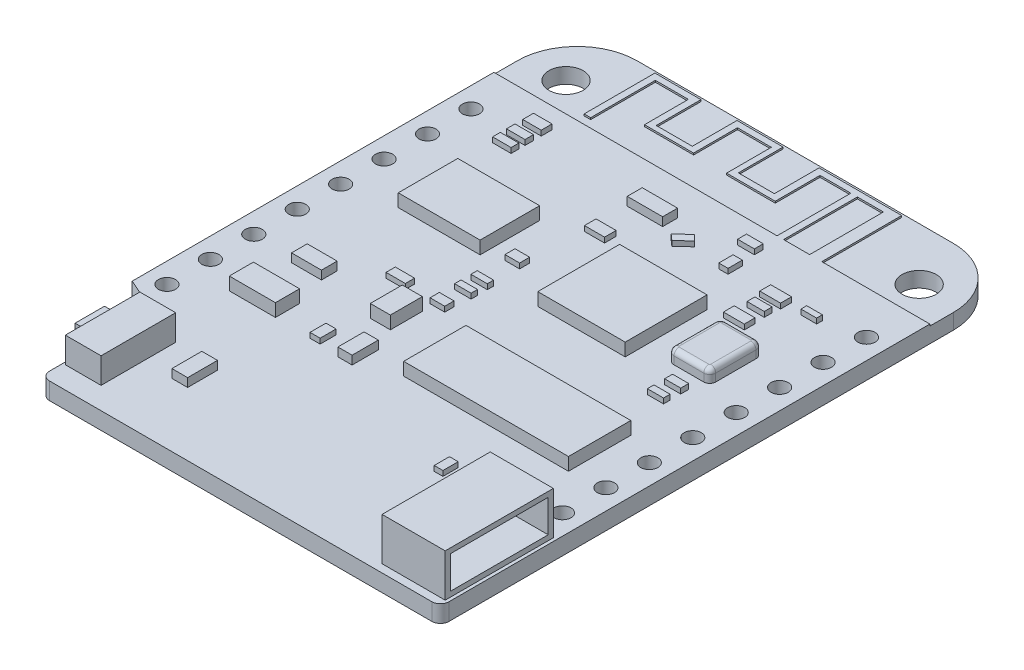
SolidWorks part; units mm, degrees
ref_plane "Front Plane" through (0, 0, 0) normal (0, 0, 1) x (1, 0, 0)
ref_plane "Top Plane" through (0, 0, 0) normal (0, 1, 0) x (1, 0, 0)
ref_plane "Right Plane" through (0, 0, 0) normal (1, 0, 0) x (0, 0, -1)
sketch "Sketch2"
sketch "Sketch4" plane through (0, 0, 0) normal (0, 1, 0) x (1, 0, 0)
  line L4 (0, 25.3183) -> (0, -8.1817) construction
  line L5 (-9.25, 25.3183) -> (9.25, 25.3183)
  line L6 (-12.75, 21.8183) -> (-12.75, -0.7087)
  line L7 (-10.1117, -8.1817) -> (12.25, -8.1817)
  line L27 (12.75, 21.8183) -> (12.75, -7.6817)
  line L28 (-12.75, -0.7087) -> (-10.9103, -1.5185)
  line L29 (-10.6117, -1.9761) -> (-10.6117, -7.6817)
  arc A2 (-9.25, 25.3183) -> (-12.75, 21.8183) centre (-9.25, 21.8183) ccw
  arc A3 (9.25, 25.3183) -> (12.75, 21.8183) centre (9.25, 21.8183) cw
  arc A31 (12.25, -8.1817) -> (12.75, -7.6817) centre (12.25, -7.6817) ccw
  arc A32 (-10.9103, -1.5185) -> (-10.6117, -1.9761) centre (-11.1117, -1.9761) cw
  arc A33 (-10.6117, -7.6817) -> (-10.1117, -8.1817) centre (-10.1117, -7.6817) ccw
  circle A35 centre (-11.5663, 17.9202) radius 0.5
  circle A36 centre (-11.5663, 15.3802) radius 0.5
  circle A37 centre (-11.5663, 12.8402) radius 0.5
  circle A38 centre (-11.5663, 10.3002) radius 0.5
  circle A39 centre (-11.5663, 7.7602) radius 0.5
  circle A40 centre (-11.5663, 5.2202) radius 0.5
  circle A41 centre (-11.5663, 2.6802) radius 0.5
  circle A42 centre (-11.5663, 0.1402) radius 0.5
  circle A43 centre (11.5663, 0.1402) radius 0.5
  circle A44 centre (11.5663, 2.6802) radius 0.5
  circle A45 centre (11.5663, 5.2202) radius 0.5
  circle A46 centre (11.5663, 7.7602) radius 0.5
  circle A47 centre (11.5663, 10.3002) radius 0.5
  circle A48 centre (11.5663, 12.8402) radius 0.5
  circle A49 centre (11.5663, 15.3802) radius 0.5
  circle A50 centre (11.5663, 17.9202) radius 0.5
  circle A51 centre (10.3263, 22.2414) radius 1
  circle A52 centre (-10.3263, 22.2414) radius 1
  point P8 (12.75, -8.1817)
  point P13 (-12.75, 25.3183)
  point P16 (12.75, 25.3183)
  dimension "D2" = 25.5
  dimension "D3" = 3.5
  dimension "D5" = 1
  dimension "D4" = 0.5
  dimension "D7" = 2
  dimension "D6" = 8
  dimension "D1" = 33.5
extrude "Boss-Extrude1" add sketch "Sketch4" against normal blind 1
sketch "Sketch5" plane through (0, 0, 0) normal (0, 1, 0) x (1, 0, 0)
  line L1 (8.8713, -1.3896) -> (12.5632, -1.3896)
  line L2 (8.8713, -1.3896) -> (8.8713, -7.7148)
  line L3 (8.8713, -7.7148) -> (12.5632, -7.7148)
  line L4 (12.5632, -1.3896) -> (12.5632, -7.7148)
extrude "Boss-Extrude2" add sketch "Sketch5" along normal blind 2.5
sketch "Sketch6" plane through (0, 0, 0) normal (0, 1, 0) x (1, 0, 0)
  line L1 (-10.4715, -2.5352) -> (-8.3804, -2.5352)
  line L2 (-10.4715, -2.5352) -> (-10.4715, -6.8983)
  line L3 (-10.4715, -6.8983) -> (-8.3804, -6.8983)
  line L4 (-8.3804, -2.5352) -> (-8.3804, -6.8983)
extrude "Boss-Extrude3" add sketch "Sketch6" along normal blind 1.5
sketch "Sketch7" plane through (-10.4715, 0, 0) normal (-1, 0, 0) x (0, 0, 1)
  line L0 (4.7168, 1.5) -> (4.7168, 0) construction
  line L1 (3.8574, 1.0699) -> (5.5762, 1.0699)
  line L2 (3.8574, 1.0699) -> (3.8574, 0.4197)
  line L3 (3.8574, 0.4197) -> (5.5762, 0.4197)
  line L4 (5.5762, 1.0699) -> (5.5762, 0.4197)
  line L5 (2.5352, 1.5) -> (6.8983, 1.5) construction
  line L6 (1.9761, 0) -> (7.6817, 0) construction
extrude "Boss-Extrude4" add sketch "Sketch7" along normal blind 0.75
sketch "Sketch8" plane through (0, 0, 0) normal (0, 1, 0) x (1, 0, 0)
  line L1 (-8.6943, 14.2777) -> (-3.9072, 14.2777)
  line L2 (-8.6943, 14.2777) -> (-8.6943, 10.7962)
  line L3 (-8.6943, 10.7962) -> (-3.9072, 10.7962)
  line L4 (-3.9072, 14.2777) -> (-3.9072, 10.7962)
  line L5 (0.3904, 14.6585) -> (5.504, 14.6585)
  line L6 (0.3904, 14.6585) -> (0.3904, 9.8714)
  line L7 (0.3904, 9.8714) -> (5.504, 9.8714)
  line L8 (5.504, 14.6585) -> (5.504, 9.8714)
  line L9 (9.6383, 6.0634) -> (0, 6.0634)
  line L10 (9.6383, 6.0634) -> (9.6383, 2.4186)
  line L11 (9.6383, 2.4186) -> (0, 2.4186)
  line L12 (0, 6.0634) -> (0, 2.4186)
  line L13 (-9.4201, 1.6394) -> (-6.7207, 1.6394)
  line L14 (-9.4201, 1.6394) -> (-9.4201, 3.0508)
  line L15 (-9.4201, 3.0508) -> (-6.7207, 3.0508)
  line L16 (-6.7207, 1.6394) -> (-6.7207, 3.0508)
  line L17 (-2.7333, 4.3741) -> (-3.9072, 4.3741)
  line L18 (-2.7333, 4.3741) -> (-2.7333, 6.2443)
  line L19 (-2.7333, 6.2443) -> (-3.9072, 6.2443)
  line L20 (-3.9072, 4.3741) -> (-3.9072, 6.2443)
extrude "Boss-Extrude5" add sketch "Sketch8" along normal blind 0.75
sketch "Sketch9" plane through (0, 0, 0) normal (0, 1, 0) x (1, 0, 0)
  line L0 (-12.75, 21.8183) -> (-12.75, -0.7087) construction
  line L1 (-12.75, 21.8183) -> (-12.75, 20.4457)
  line L2 (12.75, -7.6817) -> (12.75, 21.8183) construction
  line L3 (12.75, 20.4457) -> (12.75, 21.8183)
  line L4 (9.25, 25.3183) -> (-9.25, 25.3183) construction
  line L5 (9.25, 25.3183) -> (-9.25, 25.3183)
  line L6 (-12.75, 20.4457) -> (3.81, 20.4457)
  line L7 (-8.004, 20.9768) -> (-8.004, 25.118)
  line L8 (-8.004, 25.118) -> (-5.3109, 25.118)
  line L9 (-5.3109, 25.118) -> (-5.3109, 22.5011)
  line L10 (-5.3109, 22.5011) -> (-3.2022, 22.5011)
  line L11 (-3.2022, 22.5011) -> (-3.2022, 25.118)
  line L12 (-3.2022, 25.118) -> (-0.5091, 25.118)
  line L13 (-0.5091, 25.118) -> (-0.5091, 22.5011)
  line L14 (-0.5091, 22.5011) -> (1.5996, 22.5011)
  line L15 (1.5996, 22.5011) -> (1.5996, 25.118)
  line L16 (1.5996, 25.118) -> (6.4269, 25.118)
  line L17 (6.4269, 25.118) -> (6.4269, 20.4457)
  line L19 (5.7155, 20.4457) -> (5.7155, 24.7623)
  line L20 (5.7155, 24.7623) -> (4.1911, 24.7623)
  line L21 (4.1911, 24.7623) -> (4.1911, 20.4457)
  line L23 (3.81, 20.4457) -> (3.81, 24.7623)
  line L24 (3.81, 24.7623) -> (2.0061, 24.7623)
  line L25 (2.0061, 24.7623) -> (2.0061, 22.1455)
  line L26 (2.0061, 22.1455) -> (-0.8394, 22.1455)
  line L27 (-0.8394, 22.1455) -> (-0.8394, 24.7623)
  line L28 (-0.8394, 24.7623) -> (-2.8211, 24.7623)
  line L29 (-2.8211, 24.7623) -> (-2.8211, 22.1963)
  line L30 (-2.8211, 22.1963) -> (-5.692, 22.1963)
  line L31 (-5.692, 22.1963) -> (-5.692, 24.7623)
  line L32 (-5.692, 24.7623) -> (-7.6229, 24.7623)
  line L33 (-7.6229, 24.7623) -> (-7.6229, 20.9768)
  line L34 (-7.6229, 20.9768) -> (-8.004, 20.9768)
  line L35 (4.1911, 20.4457) -> (5.7155, 20.4457)
  line L36 (6.4269, 20.4457) -> (12.75, 20.4457)
  arc A0 (-9.25, 25.3183) -> (-12.75, 21.8183) centre (-9.25, 21.8183) ccw construction
  arc A1 (-9.25, 25.3183) -> (-12.75, 21.8183) centre (-9.25, 21.8183) ccw
  arc A2 (12.75, 21.8183) -> (9.25, 25.3183) centre (9.25, 21.8183) ccw construction
  arc A3 (12.75, 21.8183) -> (9.25, 25.3183) centre (9.25, 21.8183) ccw
  circle A4 centre (-10.3263, 22.2414) radius 1 construction
  circle A5 centre (-10.3263, 22.2414) radius 1
  circle A6 centre (10.3263, 22.2414) radius 1 construction
  circle A7 centre (10.3263, 22.2414) radius 1
extrude "Cut-Extrude1" cut sketch "Sketch9" against normal blind 0.1 contours L21 L35 L19 L20 | L3 A3 L5 A1 L1 L6 L23 L24 L25 L26 L27 L28 L29 L30 L31 L32 L33 L34 L7 L8 L9 L10 L11 L12 L13 L14 L15 L16 L17 L36 A7 A5
sketch "Sketch10" plane through (0, 0, 0) normal (0, 1, 0) x (1, 0, 0)
  line L1 (-6.6609, -2.725) -> (-5.7426, -2.725)
  line L2 (-6.6609, -2.725) -> (-6.6609, -4.4741)
  line L3 (-6.6609, -4.4741) -> (-5.7426, -4.4741)
  line L4 (-5.7426, -2.725) -> (-5.7426, -4.4741)
  line L5 (-2.9003, 3.0032) -> (-2.0695, 3.0032)
  line L6 (-2.9003, 3.0032) -> (-2.9003, 1.4728)
  line L7 (-2.9003, 1.4728) -> (-2.0695, 1.4728)
  line L8 (-2.0695, 3.0032) -> (-2.0695, 1.4728)
  line L9 (-9.0221, 5.8017) -> (-7.273, 5.8017)
  line L10 (-9.0221, 5.8017) -> (-9.0221, 4.8834)
  line L11 (-9.0221, 4.8834) -> (-7.273, 4.8834)
  line L12 (-7.273, 5.8017) -> (-7.273, 4.8834)
  line L13 (-2.0695, 18.4388) -> (0, 18.4388)
  line L14 (-2.0695, 18.4388) -> (-2.0695, 17.5642)
  line L15 (-2.0695, 17.5642) -> (0, 17.5642)
  line L16 (0, 18.4388) -> (0, 17.5642)
extrude "Boss-Extrude6" add sketch "Sketch10" along normal blind 0.5
sketch "Sketch11" plane through (0, 0, 0) normal (0, 1, 0) x (1, 0, 0)
  line L1 (-9.219, 19.2321) -> (-8.1353, 19.2321)
  line L2 (-9.219, 19.2321) -> (-9.219, 18.6)
  line L3 (-9.219, 18.6) -> (-8.1353, 18.6)
  line L4 (-8.1353, 19.2321) -> (-8.1353, 18.6)
  line L5 (-9.219, 18.1485) -> (-8.1353, 18.1485)
  line L6 (-9.219, 18.1485) -> (-9.219, 17.6518)
  line L7 (-9.219, 17.6518) -> (-8.1353, 17.6518)
  line L8 (-8.1353, 18.1485) -> (-8.1353, 17.6518)
  line L9 (-9.219, 17.2906) -> (-8.1353, 17.2906)
  line L10 (-9.219, 17.2906) -> (-9.219, 16.8391)
  line L11 (-9.219, 16.8391) -> (-8.1353, 16.8391)
  line L12 (-8.1353, 17.2906) -> (-8.1353, 16.8391)
  line L13 (3.7847, 17.9002) -> (4.3265, 17.9002)
  line L14 (3.7847, 17.9002) -> (3.7847, 17.0649)
  line L15 (3.7847, 17.0649) -> (4.3265, 17.0649)
  line L16 (4.3265, 17.9002) -> (4.3265, 17.0649)
  line L17 (6.4035, 17.4825) -> (7.6226, 17.4825)
  line L18 (6.4035, 17.4825) -> (6.4035, 16.8391)
  line L19 (6.4035, 16.8391) -> (7.6226, 16.8391)
  line L20 (7.6226, 17.4825) -> (7.6226, 16.8391)
  line L21 (6.4035, 15.3491) -> (7.6226, 15.3491)
  line L22 (6.4035, 15.3491) -> (6.4035, 14.717)
  line L23 (6.4035, 14.717) -> (7.6226, 14.717)
  line L24 (7.6226, 15.3491) -> (7.6226, 14.717)
  line L25 (-2.0399, 15.7103) -> (-0.8659, 15.7103)
  line L26 (-2.0399, 15.7103) -> (-2.0399, 15.033)
  line L27 (-2.0399, 15.033) -> (-0.8659, 15.033)
  line L28 (-0.8659, 15.7103) -> (-0.8659, 15.033)
  line L29 (-2.8977, 11.8273) -> (-2.0399, 11.8273)
  line L30 (-2.8977, 11.8273) -> (-2.8977, 11.2403)
  line L31 (-2.8977, 11.2403) -> (-2.0399, 11.2403)
  line L32 (-2.0399, 11.8273) -> (-2.0399, 11.2403)
  line L33 (-5.4714, 7.4024) -> (-4.3426, 7.4024)
  line L34 (-5.4714, 7.4024) -> (-5.4714, 6.8606)
  line L35 (-5.4714, 6.8606) -> (-4.3426, 6.8606)
  line L36 (-4.3426, 7.4024) -> (-4.3426, 6.8606)
  line L37 (-2.8977, 7.4024) -> (-2.0399, 7.4024)
  line L38 (-2.8977, 7.4024) -> (-2.8977, 6.8606)
  line L39 (-2.8977, 6.8606) -> (-2.0399, 6.8606)
  line L40 (-2.0399, 7.4024) -> (-2.0399, 6.8606)
  line L41 (-4.6563, 2.5319) -> (-4.0653, 2.5319)
  line L42 (-4.6563, 2.5319) -> (-4.6563, 1.5988)
  line L43 (-4.6563, 1.5988) -> (-4.0653, 1.5988)
  line L44 (-4.0653, 2.5319) -> (-4.0653, 1.5988)
  line L45 (5.7178, -0.6193) -> (6.228, -0.6193)
  line L46 (5.7178, -0.6193) -> (5.7178, -1.5121)
  line L47 (5.7178, -1.5121) -> (6.228, -1.5121)
  line L48 (6.228, -0.6193) -> (6.228, -1.5121)
extrude "Boss-Extrude7" add sketch "Sketch11" along normal blind 0.3
sketch "Sketch12" plane through (0, 0, 0) normal (0, 1, 0) x (1, 0, 0)
  line L0 (0.9262, 17.1356) -> (1.6302, 17.809)
  line L1 (3.1301, 19.3395) -> (4.1097, 19.3395)
  line L2 (3.1301, 19.3395) -> (3.1301, 18.8192)
  line L3 (3.1301, 18.8192) -> (4.1097, 18.8192)
  line L4 (4.1097, 19.3395) -> (4.1097, 18.8192)
  line L5 (1.6302, 17.809) -> (1.9523, 17.4723)
  line L6 (1.9523, 17.4723) -> (1.2782, 16.8275)
  line L7 (1.2782, 16.8275) -> (0.9262, 17.1356)
  line L9 (8.5175, 17.4723) -> (9.4359, 17.4723)
  line L10 (8.5175, 17.4723) -> (8.5175, 17.1356)
  line L11 (8.5175, 17.1356) -> (9.4359, 17.1356)
  line L12 (9.4359, 17.4723) -> (9.4359, 17.1356)
  line L13 (6.5585, 16.4009) -> (7.5686, 16.4009)
  line L14 (6.5585, 16.4009) -> (6.5585, 15.9418)
  line L15 (6.5585, 15.9418) -> (7.5686, 15.9418)
  line L16 (7.5686, 16.4009) -> (7.5686, 15.9418)
  line L17 (8.0621, 10.0818) -> (9.0079, 10.0818)
  line L18 (8.0621, 10.0818) -> (8.0621, 9.6147)
  line L19 (8.0621, 9.6147) -> (9.0079, 9.6147)
  line L20 (9.0079, 10.0818) -> (9.0079, 9.6147)
  line L21 (8.0621, 8.9958) -> (9.0079, 8.9958)
  line L22 (8.0621, 8.9958) -> (8.0621, 8.6104)
  line L23 (8.0621, 8.6104) -> (9.0079, 8.6104)
  line L24 (9.0079, 8.9958) -> (9.0079, 8.6104)
  line L25 (-2.8925, 9.6147) -> (-1.9313, 9.6147)
  line L26 (-2.8925, 9.6147) -> (-2.8925, 9.2438)
  line L27 (-2.8925, 9.2438) -> (-1.9313, 9.2438)
  line L28 (-1.9313, 9.6147) -> (-1.9313, 9.2438)
  line L29 (-2.8925, 8.6689) -> (-1.9313, 8.6689)
  line L30 (-2.8925, 8.6689) -> (-2.8925, 8.292)
  line L31 (-2.8925, 8.292) -> (-1.9313, 8.292)
  line L32 (-1.9313, 8.6689) -> (-1.9313, 8.292)
  line L33 (6.7826, -0.6164) -> (7.2972, -0.6164)
  line L34 (6.7826, -0.6164) -> (6.7826, -1.5004)
  line L35 (6.7826, -1.5004) -> (7.2972, -1.5004)
  line L36 (7.2972, -0.6164) -> (7.2972, -1.5004)
extrude "Boss-Extrude8" add sketch "Sketch12" along normal blind 0.3
sketch "Sketch13" plane through (0, 0, 0) normal (0, 1, 0) x (1, 0, 0)
  line L1 (7.3356, 13.9511) -> (9.0733, 13.9511)
  line L2 (6.9856, 13.6011) -> (6.9856, 11.2463)
  line L3 (7.3356, 10.8963) -> (9.0733, 10.8963)
  line L4 (9.4233, 13.6011) -> (9.4233, 11.2463)
  arc A0 (6.9856, 11.2463) -> (7.3356, 10.8963) centre (7.3356, 11.2463) ccw
  arc A1 (9.0733, 10.8963) -> (9.4233, 11.2463) centre (9.0733, 11.2463) ccw
  arc A2 (9.0733, 13.9511) -> (9.4233, 13.6011) centre (9.0733, 13.6011) cw
  arc A3 (7.3356, 13.9511) -> (6.9856, 13.6011) centre (7.3356, 13.6011) ccw
  dimension "D1" = 0.35
extrude "Boss-Extrude9" add sketch "Sketch13" along normal up to vertex (0.75 mm away)
fillet "Fillet1" radius 0.3 8 edges at (6.9856, 0.75, -12.4237) (7.0881, 0.75, -13.8486) (8.2044, 0.75, -13.9511) (9.3208, 0.75, -13.8486) (9.4233, 0.75, -12.4237) (9.3208, 0.75, -10.9988) (8.2044, 0.75, -10.8963) (7.0881, 0.75, -10.9988)
sketch "Sketch14" plane through (12.5632, 0, 0) normal (1, 0, 0) x (0, 0, -1)
  line L12 (-7.4148, 0.3) -> (-1.6896, 0.3)
  line L13 (-1.6896, 0.3) -> (-1.6896, 2.2)
  line L14 (-1.6896, 2.2) -> (-7.4148, 2.2)
  line L15 (-7.4148, 2.2) -> (-7.4148, 0.3)
  line L16 (-7.4148, 0.3) -> (-1.6896, 0.3)
  line L17 (-1.6896, 0.3) -> (-1.6896, 2.2)
  line L18 (-1.6896, 2.2) -> (-7.4148, 2.2)
  line L19 (-7.4148, 2.2) -> (-7.4148, 0.3)
  dimension "D1" = 0.3
extrude "Cut-Extrude2" cut sketch "Sketch14" against normal blind 2.3
